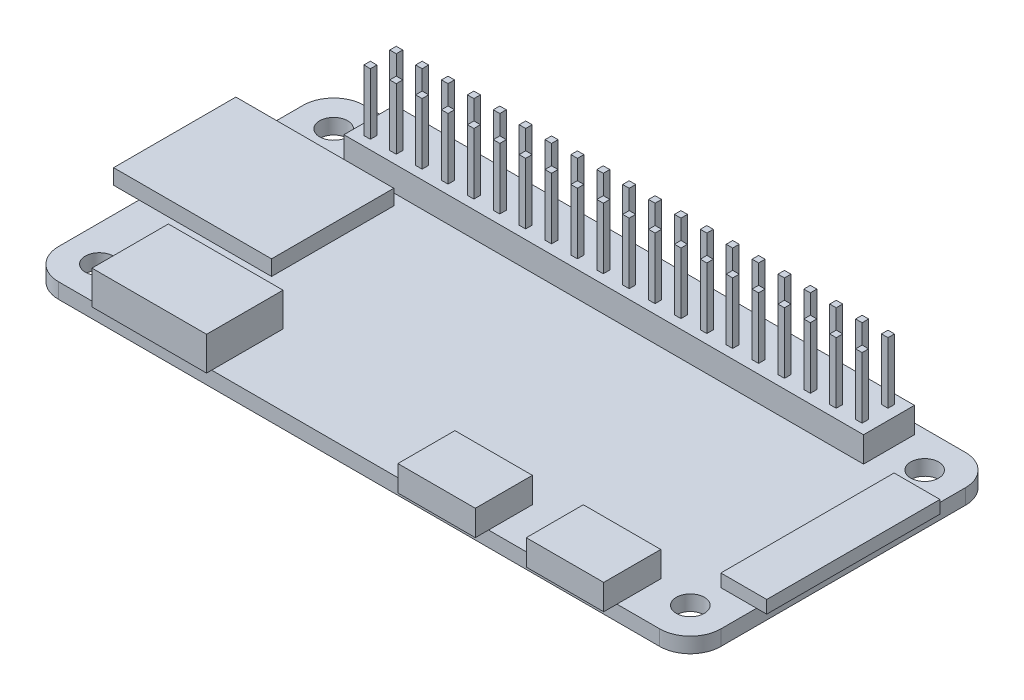
SolidWorks part; units mm, degrees
ref_plane "Front Plane" through (0, 0, 0) normal (0, 0, 1) x (1, 0, 0)
ref_plane "Top Plane" through (0, 0, 0) normal (0, 1, 0) x (1, 0, 0)
ref_plane "Right Plane" through (0, 0, 0) normal (1, 0, 0) x (0, 0, -1)
sketch "Sketch1" plane through (0, 0, 0) normal (0, 1, 0) x (1, 0, 0)
  line L1 (-32.5, -15) -> (32.5, -15)
  line L2 (-32.5, -15) -> (-32.5, 15)
  line L3 (-32.5, 15) -> (32.5, 15)
  line L4 (32.5, -15) -> (32.5, 15)
  line L5 (-32.5, -15) -> (32.5, 15) construction
  line L6 (-32.5, 15) -> (32.5, -15) construction
  point P0 (0, 0)
  dimension "D1" = 30
  dimension "D2" = 65
extrude "Boss-Extrude1" add sketch "Sketch1" along normal blind 1.5
sketch "Sketch2" plane through (0, 1.5, 0) normal (0, 1, 0) x (1, 0, 0)
  line L0 (32.5, -15) -> (32.5, 15) construction
  line L1 (-32.5, -15) -> (32.5, -15) construction
  line L2 (-32.5, 15) -> (-32.5, -15) construction
  line L3 (32.5, 15) -> (-32.5, 15) construction
  line L4 (32.5, -12) -> (32.5, 12)
  line L5 (-29.5, -15) -> (29.5, -15)
  line L6 (-32.5, 12) -> (-32.5, -12)
  line L7 (29.5, 15) -> (-29.5, 15)
  arc A0 (-29.5, -15) -> (-32.5, -12) centre (-29.5, -12) cw
  arc A1 (32.5, -12) -> (29.5, -15) centre (29.5, -12) cw
  arc A2 (32.5, 12) -> (29.5, 15) centre (29.5, 12) ccw
  arc A3 (-32.5, 12) -> (-29.5, 15) centre (-29.5, 12) cw
  dimension "D1" = 3
extrude "Cut-Extrude2" cut sketch "Sketch2" against normal through all flip side to cut
sketch "Sketch3" plane through (0, 1.5, 0) normal (0, 1, 0) x (1, 0, 0)
  line L0 (-32.5, 0) -> (32.5, 0) construction
  line L1 (-32.5, 12) -> (-32.5, -12) construction
  line L2 (32.5, -12) -> (32.5, 12) construction
  line L3 (0, -15) -> (0, 15) construction
  line L4 (-29.5, -15) -> (29.5, -15) construction
  line L5 (29.5, 15) -> (-29.5, 15) construction
  circle A0 centre (-29, 11.5) radius 1.375
  circle A1 centre (29, 11.5) radius 1.375
  circle A2 centre (29, -11.5) radius 1.375
  circle A3 centre (-29, -11.5) radius 1.375
  dimension "D1" = 2.75
  dimension "D2" = 29
  dimension "D3" = 3.5
extrude "Cut-Extrude3" cut sketch "Sketch3" against normal through all
sketch "Sketch4" plane through (0, 1.5, 0) normal (0, 1, 0) x (1, 0, 0)
  line L0 (-32.5, 12) -> (-32.5, -12) construction
  line L1 (17.7, -10.7) -> (25.3, -10.7)
  line L2 (17.7, -10.7) -> (17.7, -16.3)
  line L3 (17.7, -16.3) -> (25.3, -16.3)
  line L4 (25.3, -10.7) -> (25.3, -16.3)
  line L5 (17.7, -10.7) -> (25.3, -16.3) construction
  line L6 (17.7, -16.3) -> (25.3, -10.7) construction
  line L7 (-29.5, -15) -> (29.5, -15) construction
  line L9 (5.1, -10.7) -> (12.7, -10.7)
  line L10 (5.1, -10.7) -> (5.1, -16.3)
  line L11 (5.1, -16.3) -> (12.7, -16.3)
  line L12 (12.7, -10.7) -> (12.7, -16.3)
  line L13 (5.1, -10.7) -> (12.7, -16.3) construction
  line L14 (5.1, -16.3) -> (12.7, -10.7) construction
  point P0 (21.5, -13.5)
  point P9 (8.9, -13.5)
  dimension "D1" = 5.6
  dimension "D2" = 7.6
  dimension "D3" = 54
  dimension "D4" = 4.3
  dimension "D5" = 5.6
  dimension "D6" = 7.6
  dimension "D7" = 41.4
extrude "Boss-Extrude2" add sketch "Sketch4" along normal blind 2.5
sketch "Sketch5" plane through (0, 1.5, 0) normal (0, 1, 0) x (1, 0, 0)
  line L0 (-32.5, 12) -> (-32.5, -12) construction
  line L1 (-25.725, -8) -> (-14.475, -8)
  line L2 (-25.725, -8) -> (-25.725, -15.5)
  line L3 (-25.725, -15.5) -> (-14.475, -15.5)
  line L4 (-14.475, -8) -> (-14.475, -15.5)
  line L5 (-25.725, -8) -> (-14.475, -15.5) construction
  line L6 (-25.725, -15.5) -> (-14.475, -8) construction
  line L7 (-29.5, -15) -> (5.1, -15) construction
  point P0 (-20.1, -11.75)
  dimension "D1" = 7.5
  dimension "D2" = 11.25
  dimension "D3" = 12.4
  dimension "D4" = 0.5
extrude "Boss-Extrude3" add sketch "Sketch5" along normal blind 3.3
sketch "Sketch6" plane through (0, 1.5, 0) normal (0, 1, 0) x (1, 0, 0)
  line L0 (-32.5, 12) -> (-32.5, -12) construction
  line L1 (-35, 7.9) -> (-19.5, 7.9)
  line L2 (-35, 7.9) -> (-35, -4.1)
  line L3 (-35, -4.1) -> (-19.5, -4.1)
  line L4 (-19.5, 7.9) -> (-19.5, -4.1)
  line L5 (-35, 7.9) -> (-19.5, -4.1) construction
  line L6 (-35, -4.1) -> (-19.5, 7.9) construction
  line L7 (-29.5, -15) -> (-25.725, -15) construction
  point P0 (-27.25, 1.9)
  dimension "D1" = 12
  dimension "D2" = 15.5
  dimension "D3" = 13
  dimension "D4" = 16.9
extrude "Boss-Extrude4" add sketch "Sketch6" along normal blind 1.5
sketch "Sketch7" plane through (0, 1.5, 0) normal (0, 1, 0) x (1, 0, 0)
  line L1 (25.5, 14) -> (-25.5, 14)
  line L2 (25.5, 14) -> (25.5, 9)
  line L3 (25.5, 9) -> (-25.5, 9)
  line L4 (-25.5, 14) -> (-25.5, 9)
  line L5 (25.5, 14) -> (-25.5, 9) construction
  line L6 (25.5, 9) -> (-25.5, 14) construction
  circle A0 centre (-29, 11.5) radius 1.375 construction
  circle A1 centre (-29, 11.5) radius 1.375
  point P0 (0, 11.5)
  point P8 (0, 0)
  point P9 (0, 0)
  dimension "D1" = 5
  dimension "D2" = 51
  dimension "D3" = 29
extrude "Boss-Extrude6" add sketch "Sketch7" along normal blind 2.5 contours L1 L4 L3 L2
sketch "Sketch9" plane through (0, 1.5, 0) normal (0, 1, 0) x (1, 0, 0)
  line L0 (32.5, -12) -> (32.5, 12) construction
  line L1 (29, 8.5) -> (33.5, 8.5)
  line L2 (29, 8.5) -> (29, -8.5)
  line L3 (29, -8.5) -> (33.5, -8.5)
  line L4 (33.5, 8.5) -> (33.5, -8.5)
  line L5 (29, 8.5) -> (33.5, -8.5) construction
  line L6 (29, -8.5) -> (33.5, 8.5) construction
  line L7 (0, 0) -> (32.5, 0) construction
  point P0 (31.25, 0)
  point P7 (32.5, 0)
  point P11 (0, 0)
  dimension "D1" = 17
  dimension "D2" = 4.5
  dimension "D3" = 1
extrude "Boss-Extrude7" add sketch "Sketch9" along normal blind 1.25
sketch "Sketch10" plane through (0, 4, 0) normal (0, 1, 0) x (1, 0, 0)
  line L0 (-25.5, 11.5) -> (25.5, 11.5) construction
  line L1 (-25.5, 14) -> (-25.5, 9) construction
  line L2 (25.5, 14) -> (25.5, 9) construction
  line L3 (-25.5, 12.77) -> (25.5, 12.77) construction
  line L4 (-25.5, 10.23) -> (25.5, 10.23) construction
  line L5 (-21.91, 13.09) -> (-21.27, 13.09)
  line L6 (-24.45, 12.45) -> (-23.81, 12.45)
  line L7 (-24.45, 12.45) -> (-24.45, 13.09)
  line L8 (-24.45, 13.09) -> (-23.81, 13.09)
  line L9 (-23.81, 12.45) -> (-23.81, 13.09)
  line L10 (-24.45, 12.45) -> (-23.81, 13.09) construction
  line L11 (-24.45, 13.09) -> (-23.81, 12.45) construction
  line L12 (-21.91, 12.45) -> (-21.91, 13.09)
  line L13 (-21.91, 12.45) -> (-21.27, 12.45)
  line L14 (-21.27, 12.45) -> (-21.27, 13.09)
  line L15 (-19.37, 13.09) -> (-18.73, 13.09)
  line L16 (-19.37, 12.45) -> (-19.37, 13.09)
  line L17 (-19.37, 12.45) -> (-18.73, 12.45)
  line L18 (-18.73, 12.45) -> (-18.73, 13.09)
  line L19 (-16.83, 13.09) -> (-16.19, 13.09)
  line L20 (-16.83, 12.45) -> (-16.83, 13.09)
  line L21 (-16.83, 12.45) -> (-16.19, 12.45)
  line L22 (-16.19, 12.45) -> (-16.19, 13.09)
  line L23 (-14.29, 13.09) -> (-13.65, 13.09)
  line L24 (-14.29, 12.45) -> (-14.29, 13.09)
  line L25 (-14.29, 12.45) -> (-13.65, 12.45)
  line L26 (-13.65, 12.45) -> (-13.65, 13.09)
  line L27 (-11.75, 13.09) -> (-11.11, 13.09)
  line L28 (-11.75, 12.45) -> (-11.75, 13.09)
  line L29 (-11.75, 12.45) -> (-11.11, 12.45)
  line L30 (-11.11, 12.45) -> (-11.11, 13.09)
  line L31 (-9.21, 13.09) -> (-8.57, 13.09)
  line L32 (-9.21, 12.45) -> (-9.21, 13.09)
  line L33 (-9.21, 12.45) -> (-8.57, 12.45)
  line L34 (-8.57, 12.45) -> (-8.57, 13.09)
  line L35 (-6.67, 13.09) -> (-6.03, 13.09)
  line L36 (-6.67, 12.45) -> (-6.67, 13.09)
  line L37 (-6.67, 12.45) -> (-6.03, 12.45)
  line L38 (-6.03, 12.45) -> (-6.03, 13.09)
  line L39 (-4.13, 13.09) -> (-3.49, 13.09)
  line L40 (-4.13, 12.45) -> (-4.13, 13.09)
  line L41 (-4.13, 12.45) -> (-3.49, 12.45)
  line L42 (-3.49, 12.45) -> (-3.49, 13.09)
  line L43 (-1.59, 13.09) -> (-0.95, 13.09)
  line L44 (-1.59, 12.45) -> (-1.59, 13.09)
  line L45 (-1.59, 12.45) -> (-0.95, 12.45)
  line L46 (-0.95, 12.45) -> (-0.95, 13.09)
  line L87 (0, 9) -> (0, 14) construction
  line L88 (25.5, 9) -> (-25.5, 9) construction
  line L89 (25.5, 14) -> (-25.5, 14) construction
  line L90 (24.45, 12.45) -> (24.45, 13.09)
  line L91 (24.45, 13.09) -> (23.81, 13.09)
  line L92 (23.81, 12.45) -> (23.81, 13.09)
  line L93 (24.45, 12.45) -> (23.81, 12.45)
  line L94 (21.91, 12.45) -> (21.91, 13.09)
  line L95 (21.91, 12.45) -> (21.27, 12.45)
  line L96 (21.27, 12.45) -> (21.27, 13.09)
  line L97 (21.91, 13.09) -> (21.27, 13.09)
  line L98 (19.37, 12.45) -> (19.37, 13.09)
  line L99 (19.37, 12.45) -> (18.73, 12.45)
  line L100 (18.73, 12.45) -> (18.73, 13.09)
  line L101 (19.37, 13.09) -> (18.73, 13.09)
  line L102 (16.83, 12.45) -> (16.83, 13.09)
  line L103 (16.83, 12.45) -> (16.19, 12.45)
  line L104 (16.19, 12.45) -> (16.19, 13.09)
  line L105 (16.83, 13.09) -> (16.19, 13.09)
  line L106 (14.29, 12.45) -> (14.29, 13.09)
  line L107 (14.29, 12.45) -> (13.65, 12.45)
  line L108 (13.65, 12.45) -> (13.65, 13.09)
  line L109 (14.29, 13.09) -> (13.65, 13.09)
  line L110 (11.75, 12.45) -> (11.75, 13.09)
  line L111 (11.75, 12.45) -> (11.11, 12.45)
  line L112 (11.11, 12.45) -> (11.11, 13.09)
  line L113 (11.75, 13.09) -> (11.11, 13.09)
  line L114 (9.21, 12.45) -> (9.21, 13.09)
  line L115 (9.21, 12.45) -> (8.57, 12.45)
  line L116 (8.57, 12.45) -> (8.57, 13.09)
  line L117 (9.21, 13.09) -> (8.57, 13.09)
  line L118 (6.67, 12.45) -> (6.67, 13.09)
  line L119 (6.67, 12.45) -> (6.03, 12.45)
  line L120 (6.03, 12.45) -> (6.03, 13.09)
  line L121 (6.67, 13.09) -> (6.03, 13.09)
  line L122 (4.13, 12.45) -> (4.13, 13.09)
  line L123 (4.13, 12.45) -> (3.49, 12.45)
  line L124 (3.49, 12.45) -> (3.49, 13.09)
  line L125 (4.13, 13.09) -> (3.49, 13.09)
  line L126 (1.59, 12.45) -> (1.59, 13.09)
  line L127 (1.59, 12.45) -> (0.95, 12.45)
  line L128 (0.95, 12.45) -> (0.95, 13.09)
  line L129 (1.59, 13.09) -> (0.95, 13.09)
  line L130 (24.45, 10.55) -> (23.81, 10.55)
  line L131 (23.81, 10.55) -> (23.81, 9.91)
  line L132 (24.45, 9.91) -> (23.81, 9.91)
  line L133 (24.45, 10.55) -> (24.45, 9.91)
  line L134 (21.91, 10.55) -> (21.27, 10.55)
  line L135 (21.27, 10.55) -> (21.27, 9.91)
  line L136 (21.91, 9.91) -> (21.27, 9.91)
  line L137 (21.91, 10.55) -> (21.91, 9.91)
  line L138 (19.37, 10.55) -> (18.73, 10.55)
  line L139 (18.73, 10.55) -> (18.73, 9.91)
  line L140 (19.37, 9.91) -> (18.73, 9.91)
  line L141 (19.37, 10.55) -> (19.37, 9.91)
  line L142 (16.83, 10.55) -> (16.19, 10.55)
  line L143 (16.19, 10.55) -> (16.19, 9.91)
  line L144 (16.83, 9.91) -> (16.19, 9.91)
  line L145 (16.83, 10.55) -> (16.83, 9.91)
  line L146 (14.29, 10.55) -> (13.65, 10.55)
  line L147 (13.65, 10.55) -> (13.65, 9.91)
  line L148 (14.29, 9.91) -> (13.65, 9.91)
  line L149 (14.29, 10.55) -> (14.29, 9.91)
  line L150 (11.75, 10.55) -> (11.11, 10.55)
  line L151 (11.11, 10.55) -> (11.11, 9.91)
  line L152 (11.75, 9.91) -> (11.11, 9.91)
  line L153 (11.75, 10.55) -> (11.75, 9.91)
  line L154 (9.21, 10.55) -> (8.57, 10.55)
  line L155 (8.57, 10.55) -> (8.57, 9.91)
  line L156 (9.21, 9.91) -> (8.57, 9.91)
  line L157 (9.21, 10.55) -> (9.21, 9.91)
  line L158 (6.67, 10.55) -> (6.03, 10.55)
  line L159 (6.03, 10.55) -> (6.03, 9.91)
  line L160 (6.67, 9.91) -> (6.03, 9.91)
  line L161 (6.67, 10.55) -> (6.67, 9.91)
  line L162 (4.13, 10.55) -> (3.49, 10.55)
  line L163 (3.49, 10.55) -> (3.49, 9.91)
  line L164 (4.13, 9.91) -> (3.49, 9.91)
  line L165 (4.13, 10.55) -> (4.13, 9.91)
  line L166 (1.59, 10.55) -> (0.95, 10.55)
  line L167 (0.95, 10.55) -> (0.95, 9.91)
  line L168 (1.59, 9.91) -> (0.95, 9.91)
  line L169 (1.59, 10.55) -> (1.59, 9.91)
  line L170 (-1.59, 10.55) -> (-1.59, 9.91)
  line L171 (-1.59, 10.55) -> (-0.95, 10.55)
  line L172 (-0.95, 10.55) -> (-0.95, 9.91)
  line L173 (-1.59, 9.91) -> (-0.95, 9.91)
  line L174 (-4.13, 10.55) -> (-4.13, 9.91)
  line L175 (-4.13, 10.55) -> (-3.49, 10.55)
  line L176 (-3.49, 10.55) -> (-3.49, 9.91)
  line L177 (-4.13, 9.91) -> (-3.49, 9.91)
  line L178 (-6.67, 10.55) -> (-6.67, 9.91)
  line L179 (-6.67, 10.55) -> (-6.03, 10.55)
  line L180 (-6.03, 10.55) -> (-6.03, 9.91)
  line L181 (-6.67, 9.91) -> (-6.03, 9.91)
  line L182 (-9.21, 10.55) -> (-9.21, 9.91)
  line L183 (-9.21, 10.55) -> (-8.57, 10.55)
  line L184 (-8.57, 10.55) -> (-8.57, 9.91)
  line L185 (-9.21, 9.91) -> (-8.57, 9.91)
  line L186 (-11.75, 10.55) -> (-11.75, 9.91)
  line L187 (-11.75, 10.55) -> (-11.11, 10.55)
  line L188 (-11.11, 10.55) -> (-11.11, 9.91)
  line L189 (-11.75, 9.91) -> (-11.11, 9.91)
  line L190 (-14.29, 10.55) -> (-14.29, 9.91)
  line L191 (-14.29, 10.55) -> (-13.65, 10.55)
  line L192 (-13.65, 10.55) -> (-13.65, 9.91)
  line L193 (-14.29, 9.91) -> (-13.65, 9.91)
  line L194 (-16.83, 10.55) -> (-16.83, 9.91)
  line L195 (-16.83, 10.55) -> (-16.19, 10.55)
  line L196 (-16.19, 10.55) -> (-16.19, 9.91)
  line L197 (-16.83, 9.91) -> (-16.19, 9.91)
  line L198 (-19.37, 10.55) -> (-19.37, 9.91)
  line L199 (-19.37, 10.55) -> (-18.73, 10.55)
  line L200 (-18.73, 10.55) -> (-18.73, 9.91)
  line L201 (-19.37, 9.91) -> (-18.73, 9.91)
  line L202 (-21.91, 10.55) -> (-21.91, 9.91)
  line L203 (-21.91, 10.55) -> (-21.27, 10.55)
  line L204 (-21.27, 10.55) -> (-21.27, 9.91)
  line L205 (-21.91, 9.91) -> (-21.27, 9.91)
  line L206 (-24.45, 9.91) -> (-23.81, 9.91)
  line L207 (-23.81, 10.55) -> (-23.81, 9.91)
  line L208 (-24.45, 10.55) -> (-23.81, 10.55)
  line L209 (-24.45, 10.55) -> (-24.45, 9.91)
  point P10 (-24.13, 12.77)
  point P97 (-1.27, 13.09)
  point P98 (1.27, 13.09)
  point P99 (-24.13, 13.09)
  point P100 (-21.59, 13.09)
  dimension "D1" = 2.54
  dimension "D2" = 0.64
  dimension "D3" = 10
  dimension "D4" = 2.54
  dimension "D5" = 2.54
extrude "Boss-Extrude8" add sketch "Sketch10" along normal blind 6
